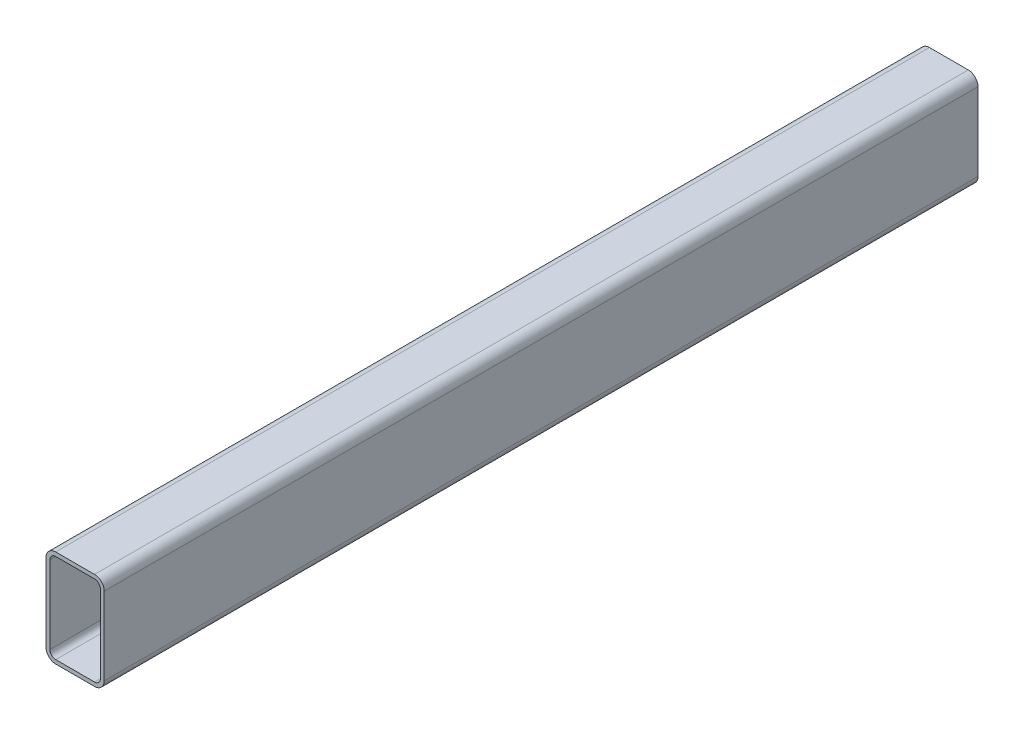
SolidWorks part; units mm, degrees
material "Plain Carbon Steel"
ref_plane "Front Plane" through (0, 0, 0) normal (0, 0, 1) x (1, 0, 0)
ref_plane "Top Plane" through (0, 0, 0) normal (0, 1, 0) x (1, 0, 0)
ref_plane "Right Plane" through (0, 0, 0) normal (1, 0, 0) x (0, 0, -1)
sketch "Sketch1" plane through (0, 0, 0) normal (0, 0, 1) x (1, 0, 0)
  line L0 (0, 73.7462) -> (0, -75.1353) construction
  line L1 (-89.5999, 0) -> (92.4117, 0) construction
  line L2 (-37.5, 0) -> (-37.5, -50)
  line L3 (-25, -62.5) -> (0, -62.5)
  line L4 (-32.5, 0) -> (-32.5, -50)
  line L5 (-25, -57.5) -> (0, -57.5)
  line L6 (-25, 57.5) -> (25, 57.5)
  line L7 (-32.5, 0) -> (-32.5, 50)
  line L8 (-25, 62.5) -> (25, 62.5)
  line L9 (-37.5, 0) -> (-37.5, 50)
  line L10 (25, -57.5) -> (0, -57.5)
  line L11 (32.5, 0) -> (32.5, -50)
  line L12 (32.5, 0) -> (32.5, 50)
  line L13 (25, -62.5) -> (0, -62.5)
  line L14 (37.5, 0) -> (37.5, -50)
  line L15 (37.5, 0) -> (37.5, 50)
  arc A0 (-37.5, -50) -> (-25, -62.5) centre (-25, -50) ccw
  arc A1 (-32.5, -50) -> (-25, -57.5) centre (-25, -50) ccw
  arc A2 (-32.5, 50) -> (-25, 57.5) centre (-25, 50) cw
  arc A3 (-37.5, 50) -> (-25, 62.5) centre (-25, 50) cw
  arc A4 (32.5, -50) -> (25, -57.5) centre (25, -50) cw
  arc A5 (32.5, 50) -> (25, 57.5) centre (25, 50) ccw
  arc A6 (37.5, -50) -> (25, -62.5) centre (25, -50) cw
  arc A7 (37.5, 50) -> (25, 62.5) centre (25, 50) ccw
  point P10 (-37.5, -62.5)
  point P31 (0, 57.5)
  point P37 (0, 62.5)
  dimension "D3" = 12.5
  dimension "D1" = 62.5
  dimension "D2" = 37.5
  dimension "D4" = 5
extrude "Boss-Extrude1" add sketch "Sketch1" along normal mid plane 1125
